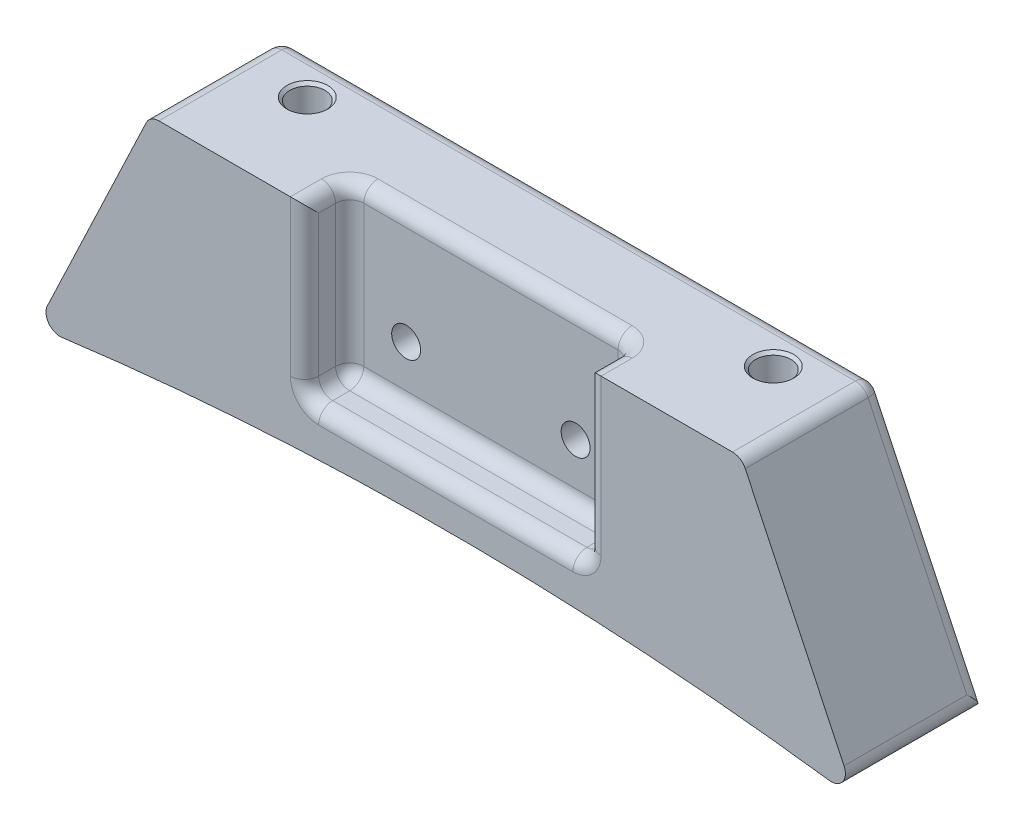
SolidWorks part; units mm, degrees
material "7075-O (SS)"
ref_plane "前视基准面" through (0, 0, 0) normal (0, 0, 1) x (1, 0, 0)
ref_plane "上视基准面" through (0, 0, 0) normal (0, 1, 0) x (1, 0, 0)
ref_plane "右视基准面" through (0, 0, 0) normal (1, 0, 0) x (0, 0, -1)
sketch "草图1" plane through (0, 0, 0) normal (0, 0, 1) x (1, 0, 0)
  line L0 (-22, 14.9488) -> (22, 14.9488)
  line L1 (-22, 14.9488) -> (-28, -3.0512) construction
  line L2 (28, -3.0512) -> (22, 14.9488) construction
  line L3 (0, 14.6299) -> (0, 0) construction
  line L4 (6, 6.9488) -> (-6, 6.9488) construction
  line L5 (0, 0) -> (30.5, 0) construction
  line L6 (30.5, 0) -> (30.5, -4) construction
  line L7 (30.5, -4) -> (-32, -4) construction
  line L8 (22, 14.9488) -> (24.5, 14.9488)
  line L9 (24.5, 14.9488) -> (29, -2.012)
  line L10 (-22, 14.9488) -> (-24.5, 14.9488)
  line L11 (-24.5, 14.9488) -> (-29, -2.012)
  arc A0 (-28, -3.0512) -> (28, -3.0512) centre (0, -130) cw construction
  circle A1 centre (-6, 6.9488) radius 0.5
  circle A2 centre (6, 6.9488) radius 0.5
  arc A3 (29, -2.012) -> (-29, -2.012) centre (0, -210) ccw
  point P10 (0, 6.9488)
  dimension "D3" = 130
  dimension "D2" = 1
  dimension "D5" = 12
  dimension "D6" = 1
  dimension "D7" = 2.5
  dimension "D8" = 8
  dimension "D12" = 210
  dimension "D1" = 44
  dimension "D4" = 56
  dimension "D9" = 18
  dimension "D10" = 2.5
  dimension "D11" = 29
  dimension "D13" = 29
extrude "凸台-拉伸1" add sketch "草图1" along normal blind 9.7
sketch "草图2" plane through (0, 14.9488, 0) normal (0, 1, 0) x (1, 0, 0)
  line L1 (24.5, 0) -> (-24.5, 0) construction
  line L2 (6, 2) -> (-6, 2)
  line L3 (6, 2) -> (6, -2)
  line L4 (6, -2) -> (-6, -2)
  line L5 (-6, 2) -> (-6, -2)
  line L6 (6, 2) -> (-6, -2) construction
  line L7 (6, -2) -> (-6, 2) construction
  point P0 (0, 0)
  dimension "D1" = 12
  dimension "D2" = 4
extrude "切除-拉伸1" [suppressed] cut sketch "草图2" against normal through all
fillet "圆角1" [suppressed] radius 1
hole_wizard "M3 螺纹孔1" positions "草图8" profile "草图9" tap size "M3" standard "GB"
sketch "草图8" plane through (0, 14.9488, 0) normal (0, 1, 0) x (-1, 0, 0)
  line L2 (-24.5, 0) -> (24.5, 0) construction
  point P0 (-16.5, 3)
  point P2 (16.5, 3)
  dimension "D1" = 33
  dimension "D2" = 16.5
  dimension "D3" = 3
sketch "草图9" plane through (16.5, 14.9488, 3) normal (1, 0, 0) x (0, 0, 1)
  line L0 (0, 0) -> (0, 8.2511)
  line L1 (0, 8.2511) -> (1.25, 7.5)
  line L2 (1.25, 7.5) -> (1.25, 0)
  line L5 (1.25, 0) -> (0, 0)
  line L10 (0, 8.2511) -> (-1.25, 7.5) construction
  line L11 (0, -6.35) -> (0, 107.95) construction
  dimension "螺纹孔钻头直径" = 2.5
  dimension "螺纹孔钻头深度" = 7.5
  dimension "导头角度" = 118
cosmetic thread "孔螺蚊线1" parameters "D1"=6, "D2"=3
cosmetic thread "孔螺蚊线3" parameters "D1"=6, "D2"=3
sketch "草图10" plane through (0, 0, 9.7) normal (0, 0, 1) x (1, 0, 0)
  line L0 (29, -2.012) -> (20.9148, 15.0031)
  line L1 (24.5, 14.9488) -> (29, -2.012)
  line L2 (20.9148, 15.0031) -> (24.5, 14.9488)
extrude "切除-拉伸2" cut sketch "草图10" against normal through all
mirror "镜向1" about plane through (0, 0, 0) normal (1, 0, 0) of "切除-拉伸2"
chamfer "倒角1" distance 0.5 angle 45 4 edges at (6.5, 6.9488, 9.7) (-5.5, 6.9488, 9.7) (6.5, 6.9488, 0) (-5.5, 6.9488, 0)
chamfer "倒角2" distance 0.2 angle 45 2 edges at (-16.5, 14.9488, 4.25) (16.5, 14.9488, 4.25)
sketch "草图11" plane through (0, 0, 9.7) normal (0, 0, 1) x (1, 0, 0)
  line L0 (20.9407, 14.9488) -> (-20.9407, 14.9488) construction
  line L1 (0, 0) -> (0, 23.5952) construction
  line L2 (-10, 14.9488) -> (10, 14.9488)
  line L3 (-10, 14.9488) -> (-10, 2.9488)
  line L4 (-10, 2.9488) -> (10, 2.9488)
  line L5 (10, 14.9488) -> (10, 2.9488)
  point P12 (0, 14.9488)
extrude "切除-拉伸3" cut sketch "草图11" against normal blind 3.2
fillet "圆角2" radius 1 11 edges at (0, 14.9488, 6.5) (-10, 14.9488, 8.1) (-10, 8.9488, 6.5) (-10, 8.9488, 9.7) (10, 8.9488, 6.5) (10, 14.9488, 8.1) (10, 8.9488, 9.7) (-10, 2.9488, 8.1) (0, 2.9488, 6.5) (10, 2.9488, 8.1) (0, 2.9488, 9.7)
sketch "草图12" plane through (0, 0, 0) normal (0, 0, -1) x (-1, 0, 0)
  line L1 (-38.9385, -22.4667) -> (31.0262, -22.4667)
  line L2 (-38.9385, -22.4667) -> (-38.9385, 27.9216)
  line L3 (-38.9385, 27.9216) -> (31.0262, 27.9216)
  line L4 (31.0262, -22.4667) -> (31.0262, 27.9216)
extrude "切除-拉伸4" [suppressed] cut sketch "草图12" against normal blind 1.5
fillet "圆角3" radius 1 7 edges at (-20.9407, 14.9488, 4.85) (20.9407, 14.9488, 4.85) (-24.9703, 6.4684, 0) (24.9703, 6.4684, 0) (0, 14.9488, 0) (-29, -2.012, 4.85) (29, -2.012, 4.85)
hole_wizard "M2.5 螺纹孔3" positions "3D草图3" profile "草图15" tap size "M2.5" standard "GB"
sketch3d "3D草图3"
  line L0 (6, 6.9488, 6.5) -> (6, 6.9488, 0.5) construction
  line L1 (-6, 6.9488, 6.5) -> (-6, 6.9488, 0.5) construction
  point P0 (6, 6.9488, 6.5)
  point P4 (-6, 6.9488, 6.5)
sketch "草图15" plane through (6, 6.9488, 6.5) normal (1, 0, 0) x (0, -1, 0)
  line L0 (0, 0) -> (0, 8.9659)
  line L1 (0, 8.9659) -> (1.025, 8.35)
  line L2 (1.025, 8.35) -> (1.025, 0)
  line L5 (1.025, 0) -> (0, 0)
  line L10 (0, 8.9659) -> (-1.025, 8.35) construction
  line L11 (0, -6.35) -> (0, 107.95) construction
  dimension "螺纹孔钻头直径" = 2.05
  dimension "螺纹孔钻头深度" = 8.35
  dimension "导头角度" = 118
cosmetic thread "孔螺蚊线6" parameters "D1"=6.7, "D2"=2.5
cosmetic thread "孔螺蚊线7" parameters "D1"=6.7, "D2"=2.5
